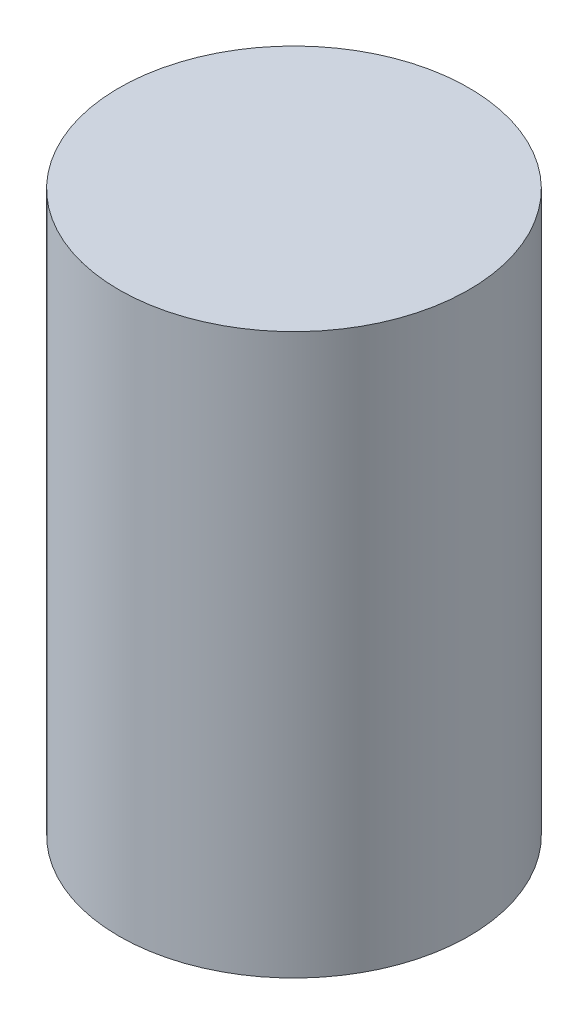
SolidWorks part; units mm, degrees
ref_plane "Спереди" through (0, 0, 0) normal (0, 0, 1) x (1, 0, 0)
ref_plane "Сверху" through (0, 0, 0) normal (0, 1, 0) x (1, 0, 0)
ref_plane "Справа" through (0, 0, 0) normal (1, 0, 0) x (0, 0, -1)
sketch "Эскиз1" plane through (0, 0, 0) normal (0, 1, 0) x (1, 0, 0)
  circle A0 centre (0, 0) radius 12.5
extrude "Вытянуть1" add sketch "Эскиз1" along normal blind 40
